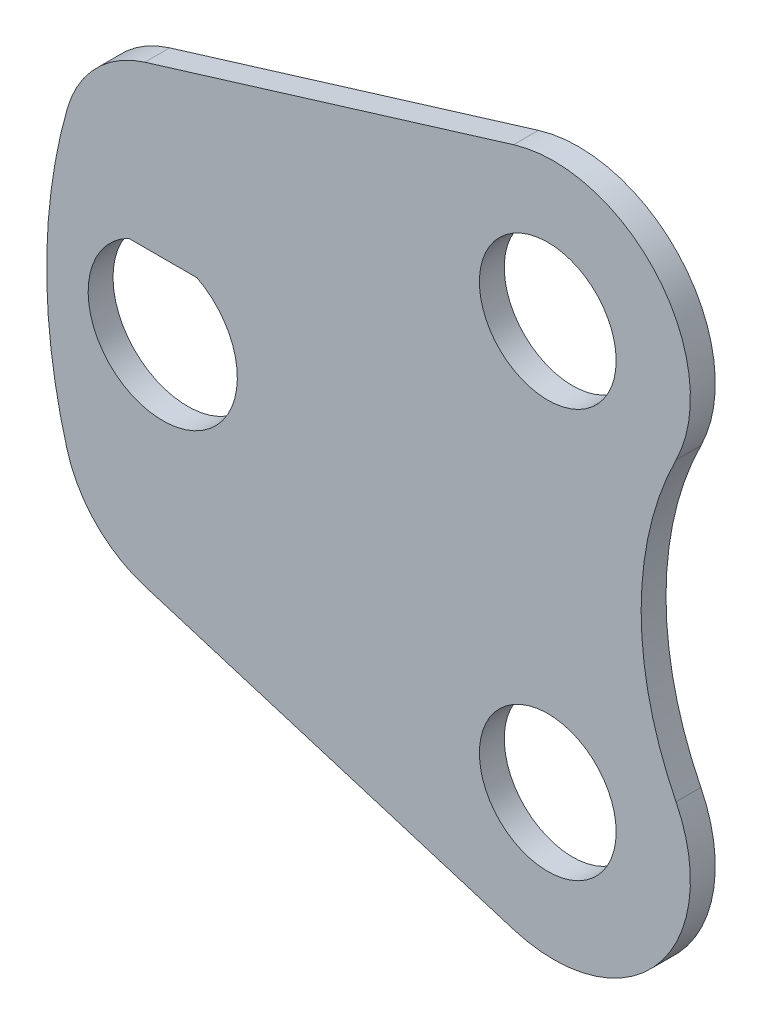
SolidWorks part; units mm, degrees
material "1.2210 (115CrV3)"
ref_plane "Ön Düzlem" through (0, 0, 0) normal (0, 0, 1) x (1, 0, 0)
ref_plane "Üst Düzlem" through (0, 0, 0) normal (0, 1, 0) x (1, 0, 0)
ref_plane "Sağ Düzlem" through (0, 0, 0) normal (1, 0, 0) x (0, 0, -1)
sketch "Sketch1" plane through (0, 0, 0) normal (0, 0, 1) x (1, 0, 0)
  line L3 (-23.6884, 4) -> (-27.8116, 4)
  line L4 (-4.5865, 20.5) -> (-26.8319, 13.687)
  line L5 (-26.8319, -13.687) -> (-4.5865, -20.5)
  arc A11 (-27.8116, 4) -> (-23.6884, 4) centre (-25.75, 0) ccw
  arc A12 (-4.5865, -20.5) -> (5.2116, -8.9286) centre (-2.1706, -12.6117) ccw
  arc A13 (5.2116, 8.9286) -> (5.2116, -8.9286) centre (23.108, 0) ccw
  arc A14 (5.2116, 8.9286) -> (-4.5865, 20.5) centre (-2.1706, 12.6117) ccw
  arc A15 (-26.8319, 13.687) -> (-31.5189, 8.8952) centre (-24.782, 6.9939) ccw
  arc A16 (-31.5189, 8.8952) -> (-31.5189, -8.8952) centre (0, 0) ccw
  arc A17 (-31.5189, -8.8952) -> (-26.8319, -13.687) centre (-24.782, -6.9939) ccw
  dimension "D1" = 32.75
  dimension "D2" = 20
  dimension "D3" = 4.5
  dimension "D4" = 41
  dimension "D5" = 7
  dimension "D10" = 34.056
  dimension "D11" = 4
  dimension "D12" = 25.75
extrude "Boss-Extrude1" add sketch "Sketch1" along normal blind 1.5
sketch "Çizim1" plane through (0, 0, 0) normal (0, 0, -1) x (-1, 0, 0)
  line L0 (0.3076, 19.5) -> (33.2469, 19.5)
  line L1 (33.2469, -19.5) -> (0.3076, -19.5)
  line L2 (33.2682, 19.5) -> (33.2682, -19.5)
  circle A0 centre (26.1042, 0) radius 3.375
  circle A1 centre (2.5242, -12.31) radius 4.125
  circle A2 centre (2.5242, 12.31) radius 4.125
  ellipse E0 centre (0.3076, 0) end of major axis (20.6986, 0) minor radius 19.5 (0.3076, 19.5) -> (0.3076, -19.5) ccw
  dimension "D1" = 8.25
  dimension "D2" = 8.25
extrude "Kes-Ekstrüzyon1" cut sketch "Çizim1" against normal mid plane 10 contours A1 | A2
